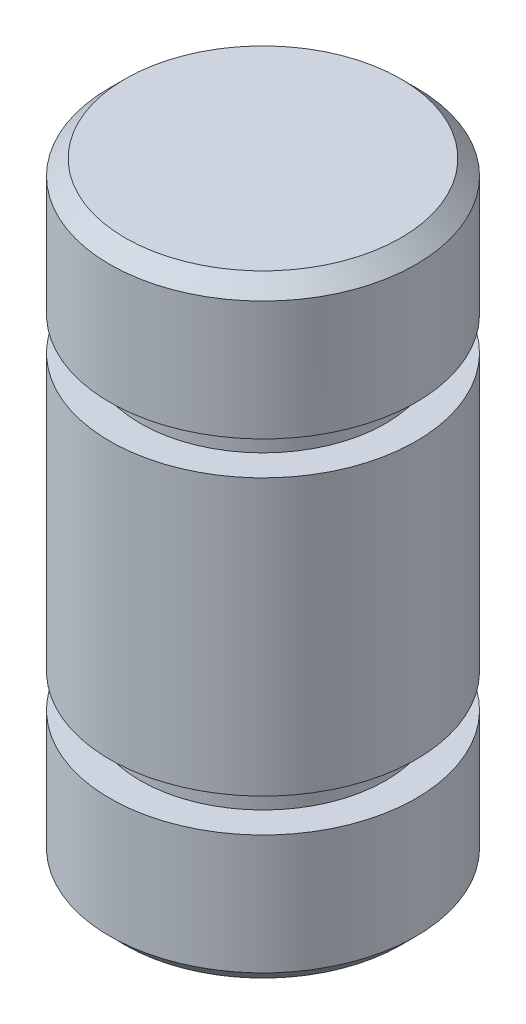
SolidWorks part; units mm, degrees
ref_plane "Ebene vorne" through (0, 0, 0) normal (0, 0, 1) x (1, 0, 0)
ref_plane "Ebene oben" through (0, 0, 0) normal (0, 1, 0) x (1, 0, 0)
ref_plane "Ebene rechts" through (0, 0, 0) normal (1, 0, 0) x (0, 0, -1)
sketch "Skizze1" plane through (0, 0, 0) normal (0, 0, 1) x (1, 0, 0)
  line L0 (0, 0) -> (0, 62.1508) construction
  line L1 (5, 5.5) -> (5, 14.5)
  line L2 (0, 0) -> (5, 0)
  line L3 (0, 0) -> (0, 20)
  line L4 (0, 20) -> (5, 20)
  line L5 (5, 0) -> (5, 4.4)
  line L6 (5, 15.6) -> (4, 15.6)
  line L8 (5, 14.5) -> (4, 14.5)
  line L9 (4, 15.6) -> (4, 14.5)
  line L10 (5, 5.5) -> (4, 5.5)
  line L12 (5, 4.4) -> (4, 4.4)
  line L13 (4, 5.5) -> (4, 4.4)
  line L14 (5, 15.6) -> (5, 20)
  line L15 (0, 10) -> (13.3913, 10) construction
  dimension "D1" = 20
  dimension "D2" = 10
  dimension "D3" = 8
  dimension "D4" = 1.1
  dimension "D5" = 9
revolve "Rotation1" add sketch "Skizze1" angle 360 about L0
chamfer "Fase1" distance 0.5 angle 45 2 edges at (0, 0, -5) (0, 20, -5)
